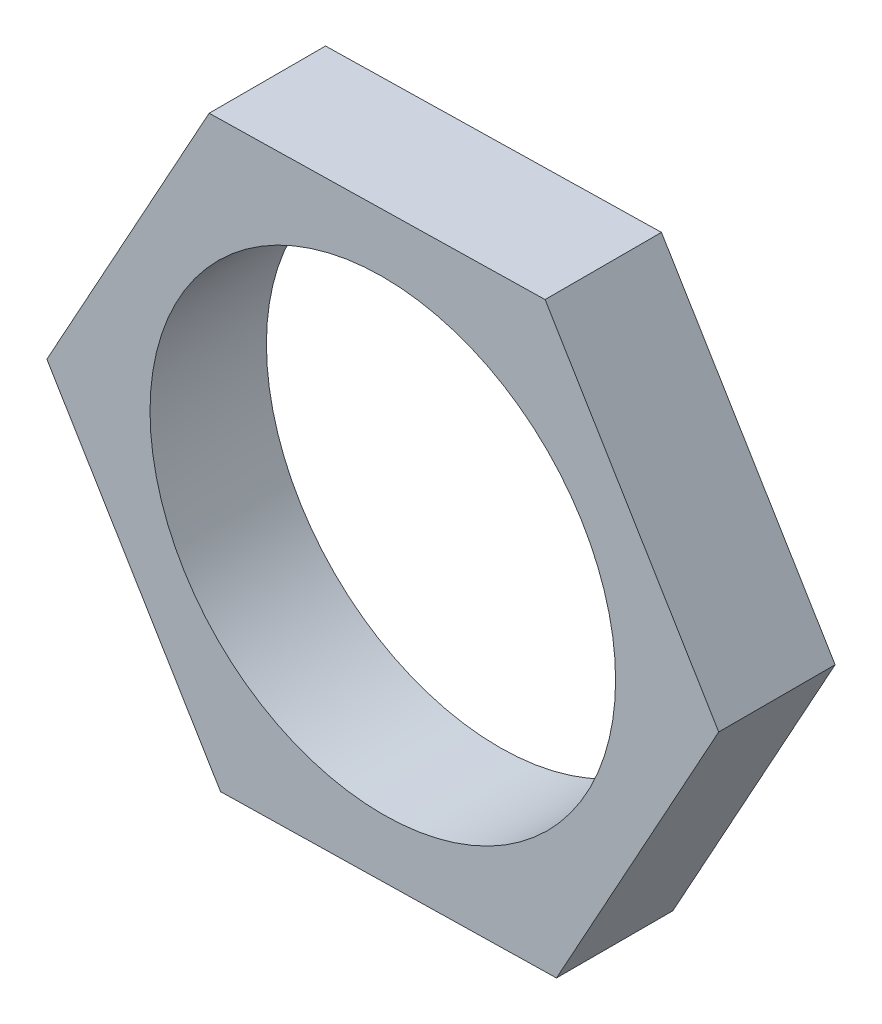
SolidWorks part; units mm, degrees
ref_plane "Front Plane" through (0, 0, 0) normal (0, 0, 1) x (1, 0, 0)
ref_plane "Top Plane" through (0, 0, 0) normal (0, 1, 0) x (1, 0, 0)
ref_plane "Right Plane" through (0, 0, 0) normal (1, 0, 0) x (0, 0, -1)
sketch "Sketch1" plane through (0, 0, 0) normal (0, 0, 1) x (1, 0, 0)
  line L1 (17.7064, 32.1024) -> (-18.9483, 31.3854)
  line L2 (-18.9483, 31.3854) -> (-36.6547, -0.717)
  line L3 (-36.6547, -0.717) -> (-17.7064, -32.1024)
  line L4 (-17.7064, -32.1024) -> (18.9483, -31.3854)
  line L5 (18.9483, -31.3854) -> (36.6547, 0.717)
  line L6 (36.6547, 0.717) -> (17.7064, 32.1024)
  circle A0 centre (0, 0) radius 31.75 construction
  circle A1 centre (0, 0) radius 25.4
  dimension "D1" = 63.5
  dimension "D2" = 50.8
extrude "Boss-Extrude1" add sketch "Sketch1" along normal blind 12.7
